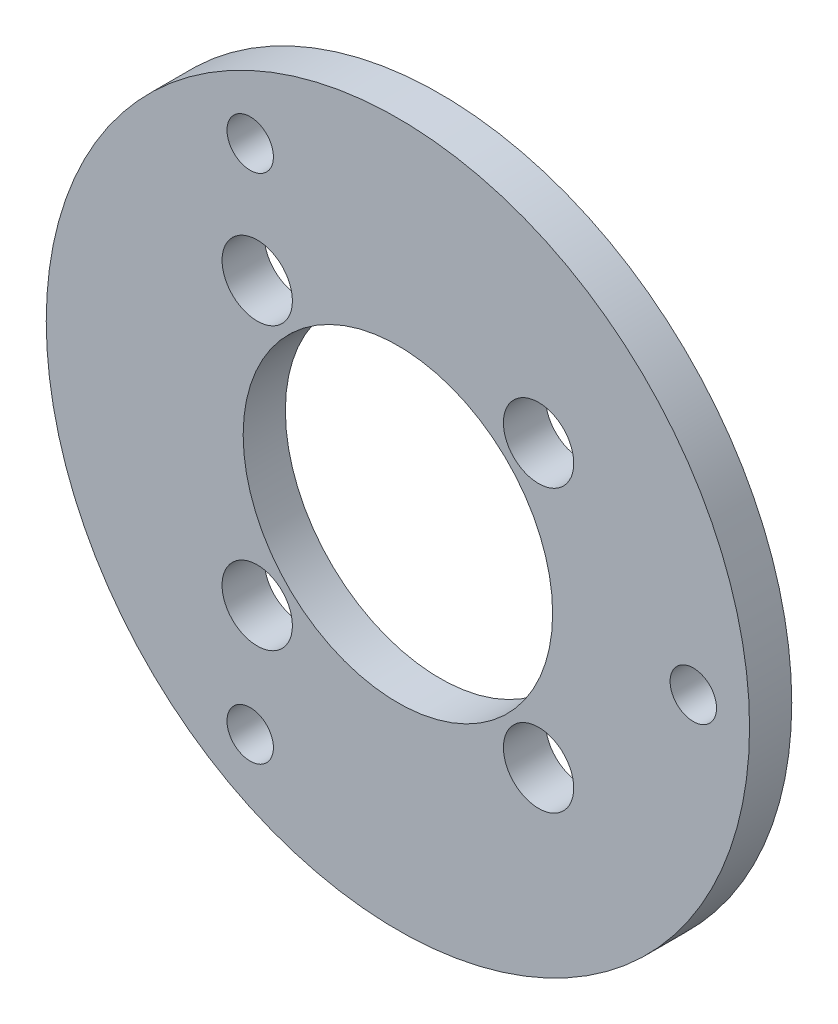
SolidWorks part; units mm, degrees
ref_plane "前视基准面" through (0, 0, 0) normal (0, 0, 1) x (1, 0, 0)
ref_plane "上视基准面" through (0, 0, 0) normal (0, 1, 0) x (1, 0, 0)
ref_plane "右视基准面" through (0, 0, 0) normal (1, 0, 0) x (0, 0, -1)
sketch "草图1" plane through (0, 0, 0) normal (0, 0, 1) x (1, 0, 0)
  line L0 (0, 0) -> (-10.5, 18.1865)
  line L1 (0, 0) -> (-10.5, -18.1865)
  circle A0 centre (0, 0) radius 21
  circle A1 centre (0, 0) radius 11
  circle A2 centre (10, 10) radius 2.5
  circle A3 centre (-10, 10) radius 2.5
  circle A4 centre (10, -10) radius 2.5
  circle A5 centre (-10, -10) radius 2.5
  circle A6 centre (21, 0) radius 1.65
  circle A7 centre (-10.5, 18.1865) radius 1.65
  circle A8 centre (-10.5, -18.1865) radius 1.65
  circle A9 centre (0, 0) radius 25
extrude "凸台-拉伸1" add sketch "草图1" along normal blind 3 contours A9 A8 A0 A7 A6 | A8 L1 A1 L0 A7 A0 A5 A3 | A8 A0 A6 A7 L0 A1 L1 A2 A4
